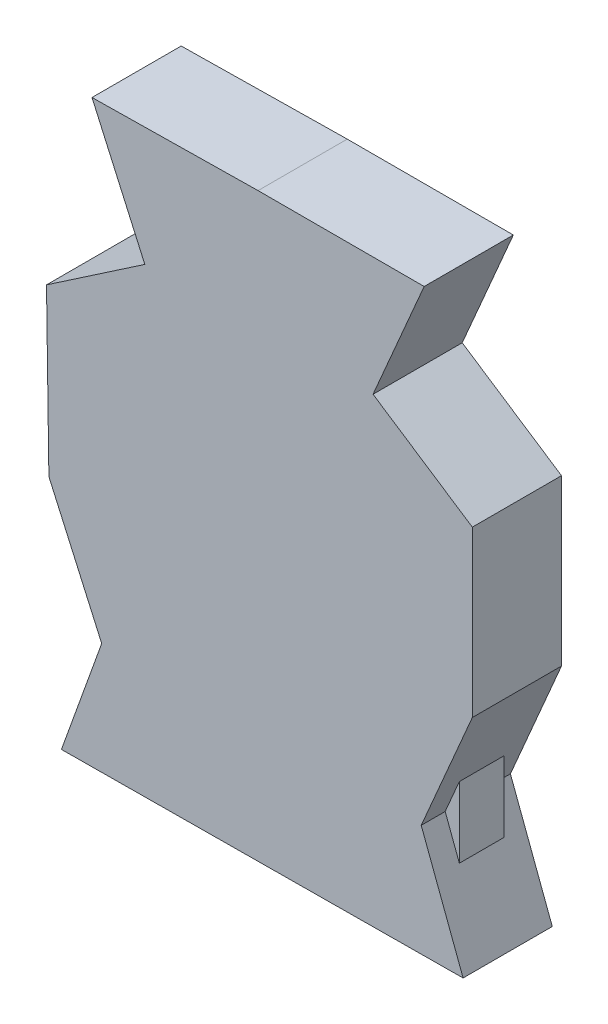
SolidWorks part; units mm, degrees
ref_plane "Front Plane" through (0, 0, 0) normal (0, 0, 1) x (1, 0, 0)
ref_plane "Top Plane" through (0, 0, 0) normal (0, 1, 0) x (1, 0, 0)
ref_plane "Right Plane" through (0, 0, 0) normal (1, 0, 0) x (0, 0, -1)
sketch "Sketch2" plane through (0, 0, 0) normal (0, 0, 1) x (1, 0, 0)
  line L16 (-35.6592, 48.9942) -> (64.2976, 48.9942) construction
  line L17 (64.2976, 48.9942) -> (64.2976, -151.0058) construction
  line L18 (64.2976, -151.0058) -> (-132.7222, -151.0058) construction
  line L23 (-132.7222, -151.0058) -> (-132.5855, 13.8223) construction
  line L28 (-35.6592, 48.9942) -> (-34.2123, -151.0058) construction
  line L29 (-132.6538, -68.5917) -> (64.2976, -68.7551) construction
  line L30 (-35.6592, 48.9942) -> (20.212, 48.9942)
  line L31 (20.212, 48.9942) -> (3.0203, 8.9942)
  line L32 (3.0203, 8.9942) -> (36.4176, -13.02)
  line L33 (36.4176, -13.02) -> (36.4176, -68.4856)
  line L34 (36.4176, -68.4856) -> (19.2259, -108.4856)
  line L35 (19.2259, -108.4856) -> (33.3181, -145.921)
  line L36 (-88.26, -109.2632) -> (-101.8092, -146.8986)
  line L37 (-106.0287, -69.5162) -> (-88.26, -109.2632)
  line L38 (-106.8312, -14.0564) -> (-106.0287, -69.5162)
  line L39 (-73.756, 8.4387) -> (-106.8312, -14.0564)
  line L40 (-91.5246, 48.1858) -> (-73.756, 8.4387)
  line L41 (-101.8092, -146.8986) -> (33.3181, -145.921)
  line L42 (-91.5246, 48.1858) -> (-35.6592, 48.9942)
  point P8 (-83.6302, -87.3522)
  point P21 (-98.1316, -22.6153)
  point P22 (-86.5495, -110.5247)
  point P23 (-106.0287, -13.02)
  dimension "D1" = 200
  dimension "D2" = 200
  dimension "D3" = 40
  dimension "D4" = 40
  dimension "D5" = 40
  dimension "D6" = 111.7396
  dimension "D7" = 135.1273
  dimension "4" = 40
extrude "Boss-Extrude1" add sketch "Sketch2" along normal blind 30
sketch "Sketch6" plane through (0, 0, 0) normal (1, 0, 0) x (0, 0, -1)
  line L0 (-6.9415, -93.5714) -> (-21.9415, -93.5714)
  line L1 (-6.9415, -93.5714) -> (-6.9415, -123.5714)
  line L2 (-6.9415, -123.5714) -> (-21.9415, -123.5714)
  line L3 (-21.9415, -93.5714) -> (-21.9415, -123.5714)
extrude "Boss-Extrude2" add sketch "Sketch6" along normal blind 24
sketch "Sketch7" plane through (24, 0, 0) normal (1, 0, 0) x (0, 0, -1)
  circle A0 centre (-14.3133, -103.729) radius 3.2885
  circle A1 centre (-14.3133, -117.0949) radius 3.5686
  dimension "D1" = 13.3659
